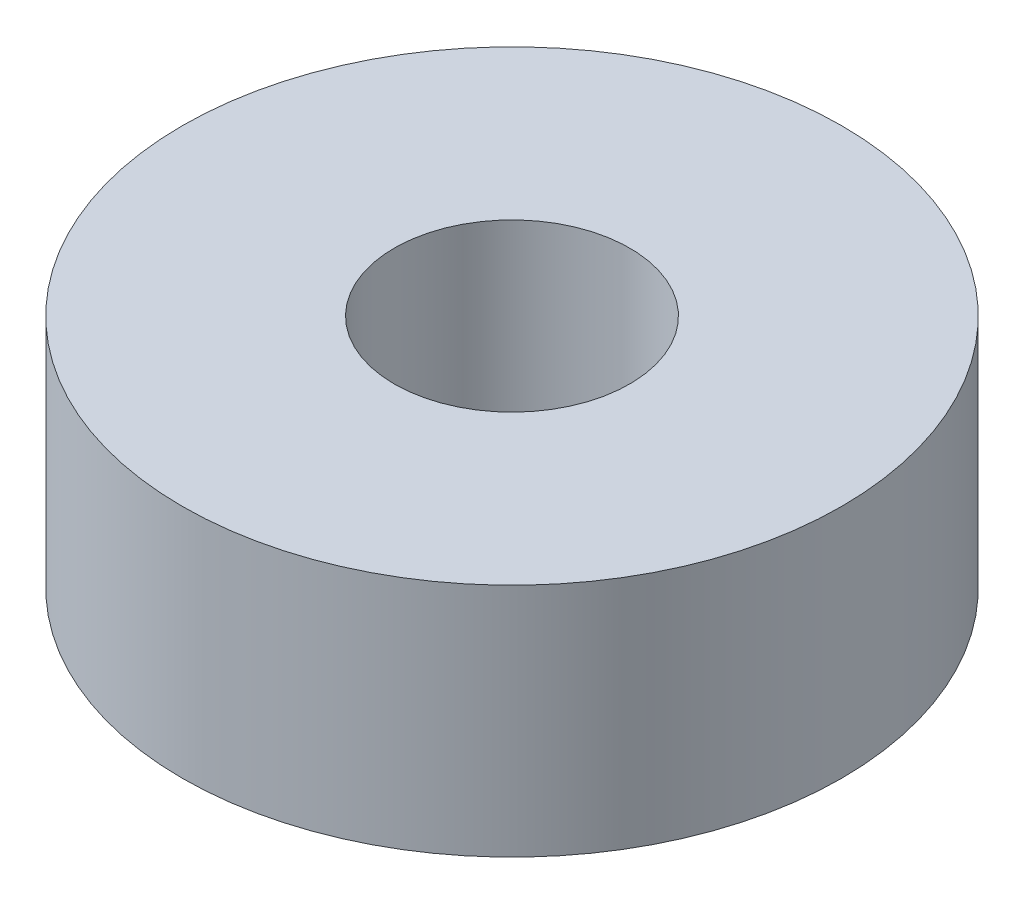
SolidWorks part; units mm, degrees
ref_plane "前视基准面" through (0, 0, 0) normal (0, 0, 1) x (1, 0, 0)
ref_plane "上视基准面" through (0, 0, 0) normal (0, 1, 0) x (1, 0, 0)
ref_plane "右视基准面" through (0, 0, 0) normal (1, 0, 0) x (0, 0, -1)
sketch "草图1" plane through (0, 0, 0) normal (0, 1, 0) x (1, 0, 0)
  circle A0 centre (0, 0) radius 2.5
  circle A1 centre (0, 0) radius 7
  dimension "D1" = 14
  dimension "D2" = 5
extrude "凸台-拉伸1" add sketch "草图1" along normal blind 5
